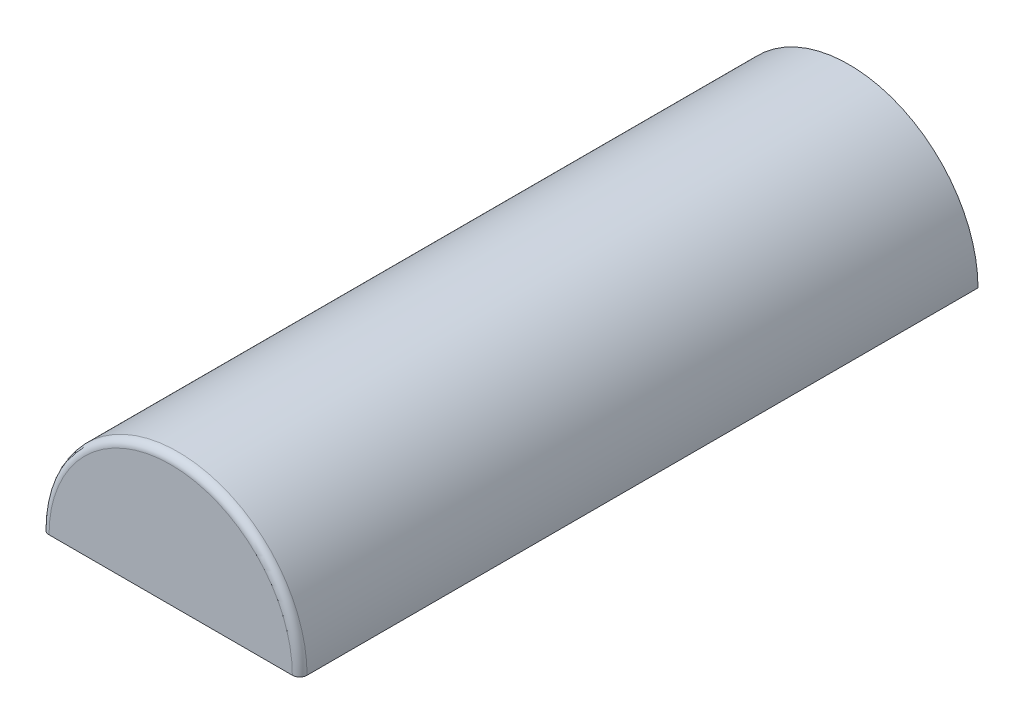
SolidWorks part; units mm, degrees
ref_plane "前视基准面" through (0, 0, 0) normal (0, 0, 1) x (1, 0, 0)
ref_plane "上视基准面" through (0, 0, 0) normal (0, 1, 0) x (1, 0, 0)
ref_plane "右视基准面" through (0, 0, 0) normal (1, 0, 0) x (0, 0, -1)
other "Configuration Table"
sketch "草图1" plane through (0, 0, 0) normal (0, 0, 1) x (1, 0, 0)
  line L0 (-175, 0) -> (175, 0)
  arc A1 (175, 0) -> (-175, 0) centre (0, 0) ccw
extrude "凸台-拉伸1" add sketch "草图1" along normal blind 920
fillet "圆角1" radius 10 1 edges at (0, 175, 920)
shell "抽壳1" thickness 2
